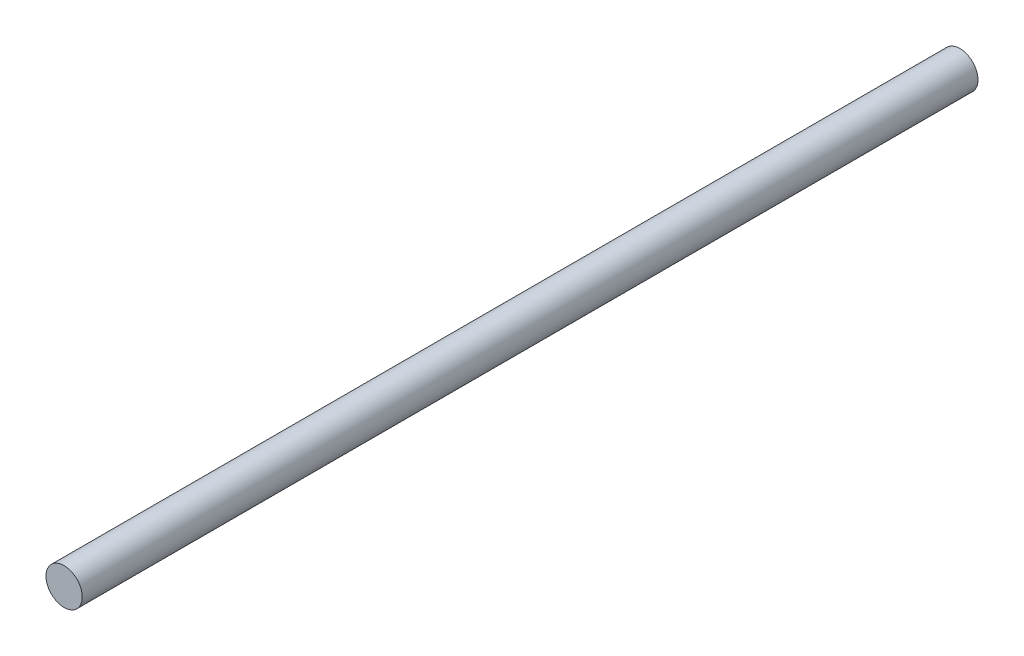
SolidWorks part; units mm, degrees
ref_plane "Alzado" through (0, 0, 0) normal (0, 0, 1) x (1, 0, 0)
ref_plane "Planta" through (0, 0, 0) normal (0, 1, 0) x (1, 0, 0)
ref_plane "Vista lateral" through (0, 0, 0) normal (1, 0, 0) x (0, 0, -1)
sketch "Croquis1" plane through (0, 0, 0) normal (0, 0, 1) x (1, 0, 0)
  circle A0 centre (0, 0) radius 4.05
  dimension "D1" = 8.1
extrude "Saliente-Extruir1" add sketch "Croquis1" along normal blind 200
